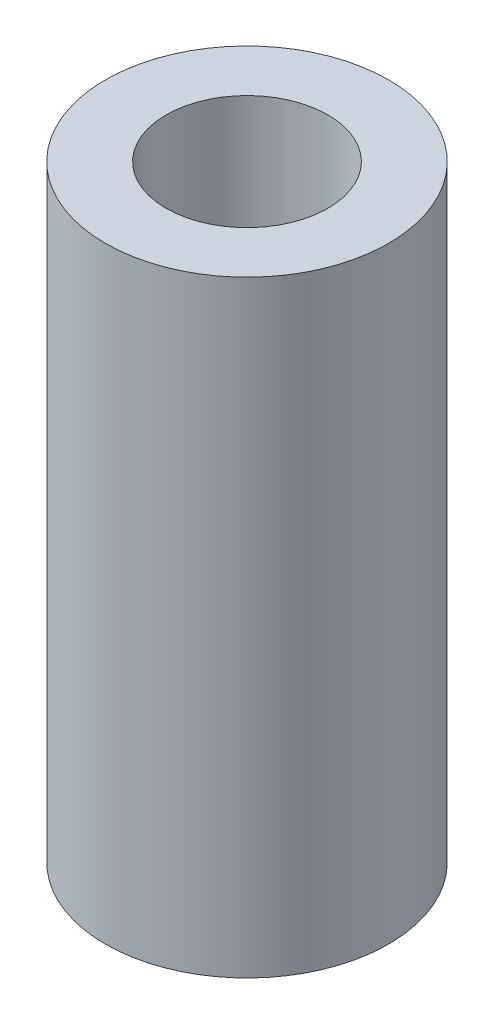
SolidWorks part; units mm, degrees
ref_plane "Front Plane" through (0, 0, 0) normal (0, 0, 1) x (1, 0, 0)
ref_plane "Top Plane" through (0, 0, 0) normal (0, 1, 0) x (1, 0, 0)
ref_plane "Right Plane" through (0, 0, 0) normal (1, 0, 0) x (0, 0, -1)
sketch "Sketch1" plane through (0, 0, 0) normal (0, 1, 0) x (1, 0, 0)
  circle A0 centre (0, 0) radius 2
  circle A1 centre (0, 0) radius 3.5
  dimension "D1" = 7
  dimension "D2" = 4
extrude "Boss-Extrude1" add sketch "Sketch1" along normal blind 15
